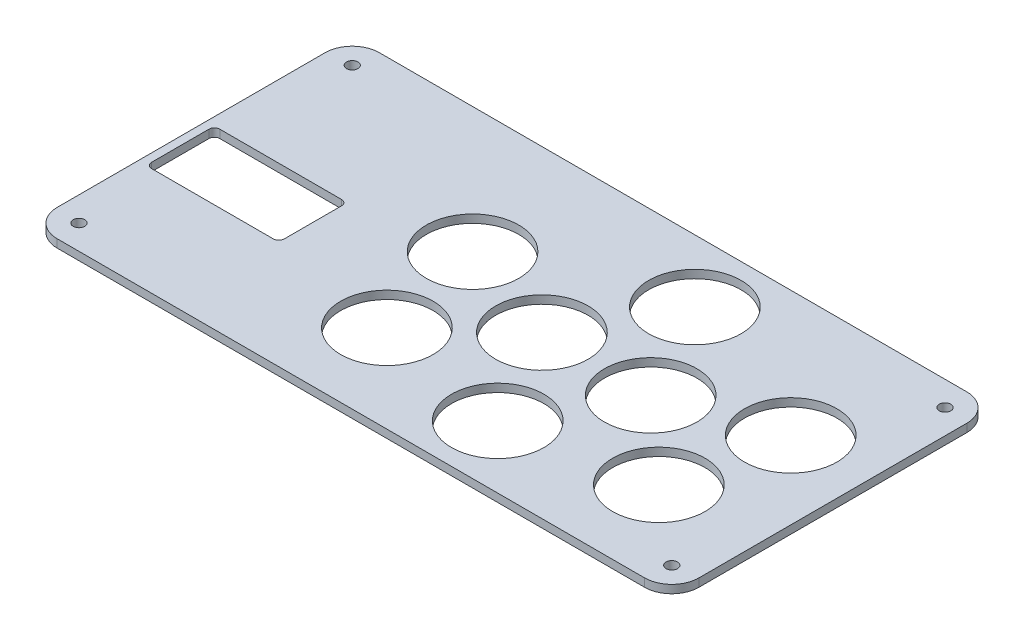
SolidWorks part; units mm, degrees
ref_plane "Front Plane" through (0, 0, 0) normal (0, 0, 1) x (1, 0, 0)
ref_plane "Top Plane" through (0, 0, 0) normal (0, 1, 0) x (1, 0, 0)
ref_plane "Right Plane" through (0, 0, 0) normal (1, 0, 0) x (0, 0, -1)
sketch "Sketch1" plane through (0, 0, 0) normal (0, 1, 0) x (1, 0, 0)
  line L0 (-50.1645, 82.8261) -> (10.8355, 82.8261) construction
  line L1 (-50.1645, 0.3261) -> (10.8355, 0.3261) construction
  line L2 (-50.1645, 0.3261) -> (-50.1645, 82.8261) construction
  line L3 (-50.1645, 82.8261) -> (10.8355, 82.8261) construction
  line L4 (10.8355, 0.3261) -> (10.8355, 82.8261) construction
  line L6 (-50.1645, 82.8261) -> (-50.1645, 0.3261) construction
  line L9 (95.3355, 77.8261) -> (95.3355, 5.3261) construction
  line L10 (95.3355, 41.5761) -> (-73.6645, 41.5761) construction
  line L11 (-53.6645, 100.8261) -> (182.3355, 100.8261)
  line L12 (-50.6645, 97.8261) -> (179.3355, 97.8261)
  line L13 (-50.6645, 97.8261) -> (-50.6645, -14.6739)
  line L14 (-50.6645, -14.6739) -> (179.3355, -14.6739)
  line L15 (179.3355, 97.8261) -> (179.3355, -14.6739)
  line L16 (182.3355, 100.8261) -> (182.3355, -17.6739)
  line L17 (-53.6645, -17.6739) -> (182.3355, -17.6739)
  line L18 (-53.6645, 100.8261) -> (-53.6645, -17.6739)
  line L19 (-50.4645, 83.1261) -> (11.1355, 83.1261)
  line L20 (11.1355, 0.0261) -> (11.1355, 83.1261)
  line L21 (-50.4645, 0.0261) -> (11.1355, 0.0261)
  line L22 (-50.4645, 83.1261) -> (-50.4645, 0.0261)
  line L23 (64.3355, 100.8261) -> (64.3355, -14.6739) construction
  line L24 (-50.6645, 22.0261) -> (-1.8645, 22.0261)
  line L25 (-50.6645, 47.1261) -> (-1.8645, 47.1261)
  line L26 (-1.8645, 47.1261) -> (-1.8645, 22.0261)
  circle A0 centre (36.8355, 54.5761) radius 17
  circle A1 centre (45.3355, 14.5761) radius 17
  circle A2 centre (145.3355, 14.5761) radius 17
  circle A4 centre (75.3355, 41.5761) radius 17
  circle A5 centre (115.3355, 41.5761) radius 17
  circle A6 centre (95.3355, 5.3261) radius 17
  circle A7 centre (153.8355, 54.5761) radius 17
  circle A8 centre (95.3355, 77.8261) radius 17
  circle A9 centre (-44.6645, -8.6739) radius 2.125
  circle A10 centre (-44.6645, 91.8261) radius 2.125
  circle A11 centre (173.3355, 91.8261) radius 2.125
  circle A12 centre (173.3355, -8.6739) radius 2.125
  point P12 (10.8355, 41.5761)
  point P27 (-50.6645, 41.5761)
  dimension "D3" = 34
  dimension "D4" = 26
  dimension "D5" = 40
  dimension "D15" = 112.5
  dimension "D20" = 82.5
  dimension "D21" = 4.25
  dimension "D22" = 9
  dimension "D23" = 9
  dimension "D1" = 61
  dimension "D2" = 82.5
  dimension "D6" = 20
  dimension "D7" = 72.5
  dimension "D8" = 36.25
  dimension "D9" = 100
  dimension "D10" = 30
  dimension "D11" = 117
  dimension "D12" = 38.5
  dimension "D13" = 40
  dimension "D14" = 27
  dimension "D16" = 230
  dimension "D17" = 3
  dimension "D18" = 0.5
  dimension "D19" = 0.3
  dimension "D24" = 22
  dimension "D25" = 13
  dimension "D26" = 36
extrude "Boss-Extrude1" add sketch "Sketch1" along normal blind 3 contours L15 L12 L13 L14 A10 A9 A8 A7 A6 A5 A4 A2 A1 A0 L22 L19 L20 L21 A11 A12 | L11 L18 L17 L16 L12 L15 L14 L13 | L25 L26 L24 L22 L21 L20 L19
fillet "Fillet1" radius 10 4 edges at (182.3355, 1.5, 17.6739) (182.3355, 1.5, -100.8261) (-53.6645, 1.5, -100.8261) (-53.6645, 1.5, 17.6739)
fillet "Fillet2" radius 2 4 edges at (-1.8645, 1.5, -22.0261) (-50.6645, 1.5, -22.0261) (-50.6645, 1.5, -47.1261) (-1.8645, 1.5, -47.1261)
